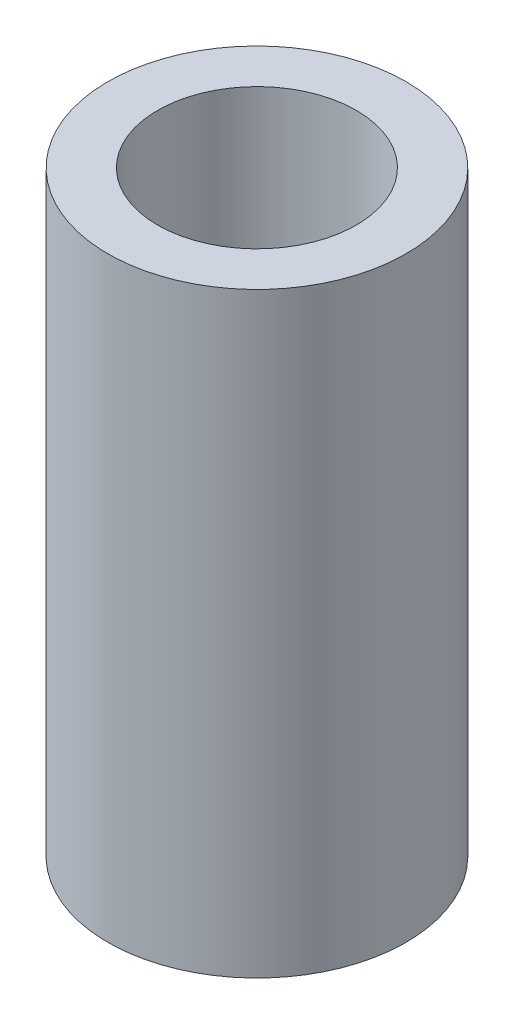
SolidWorks part; units mm, degrees
ref_plane "Front Plane" through (0, 0, 0) normal (0, 0, 1) x (1, 0, 0)
ref_plane "Top Plane" through (0, 0, 0) normal (0, 1, 0) x (1, 0, 0)
ref_plane "Right Plane" through (0, 0, 0) normal (1, 0, 0) x (0, 0, -1)
sketch "Sketch1" plane through (0, 0, 0) normal (0, 1, 0) x (1, 0, 0)
  circle A0 centre (0, 0) radius 4.7625
  circle A1 centre (0, 0) radius 3.175
  dimension "D1" = 9.525
  dimension "D2" = 6.35
extrude "Boss-Extrude1" add sketch "Sketch1" along normal blind 19.05
